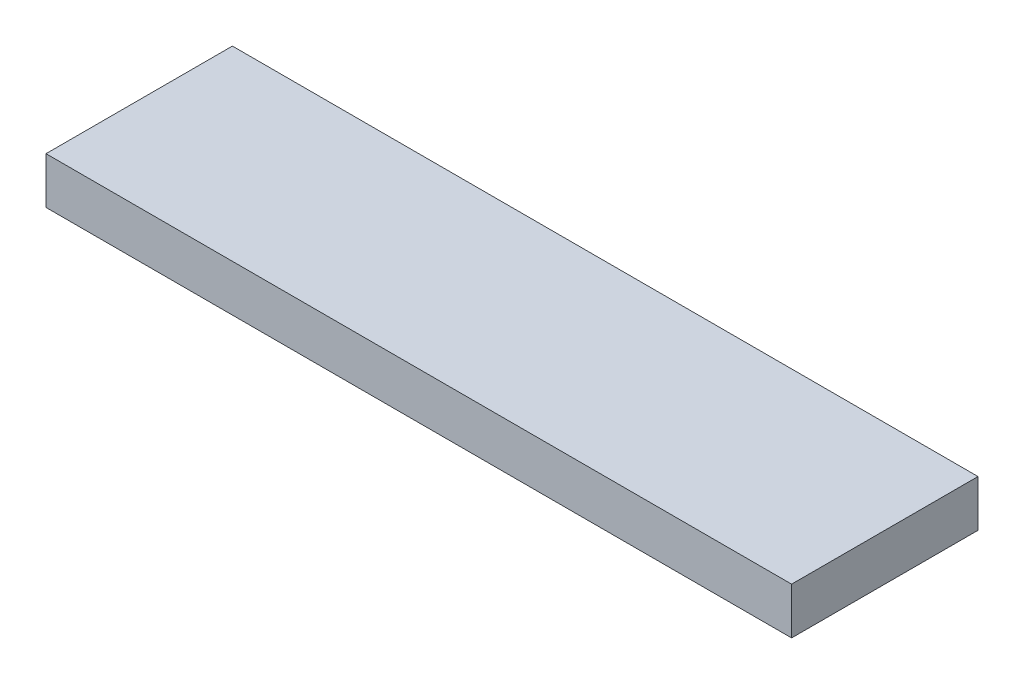
SolidWorks part; units mm, degrees
ref_plane "前视基准面" through (0, 0, 0) normal (0, 0, 1) x (1, 0, 0)
ref_plane "上视基准面" through (0, 0, 0) normal (0, 1, 0) x (1, 0, 0)
ref_plane "右视基准面" through (0, 0, 0) normal (1, 0, 0) x (0, 0, -1)
other "Configuration Table"
sketch "草图1" plane through (0, 0, 0) normal (0, 1, 0) x (1, 0, 0)
  line L1 (0, 0) -> (8, 0)
  line L2 (0, 0) -> (0, 2)
  line L3 (0, 2) -> (8, 2)
  line L4 (8, 0) -> (8, 2)
  dimension "D1" = 8
  dimension "D2" = 2
extrude "凸台-拉伸1" add sketch "草图1" along normal blind 0.5
